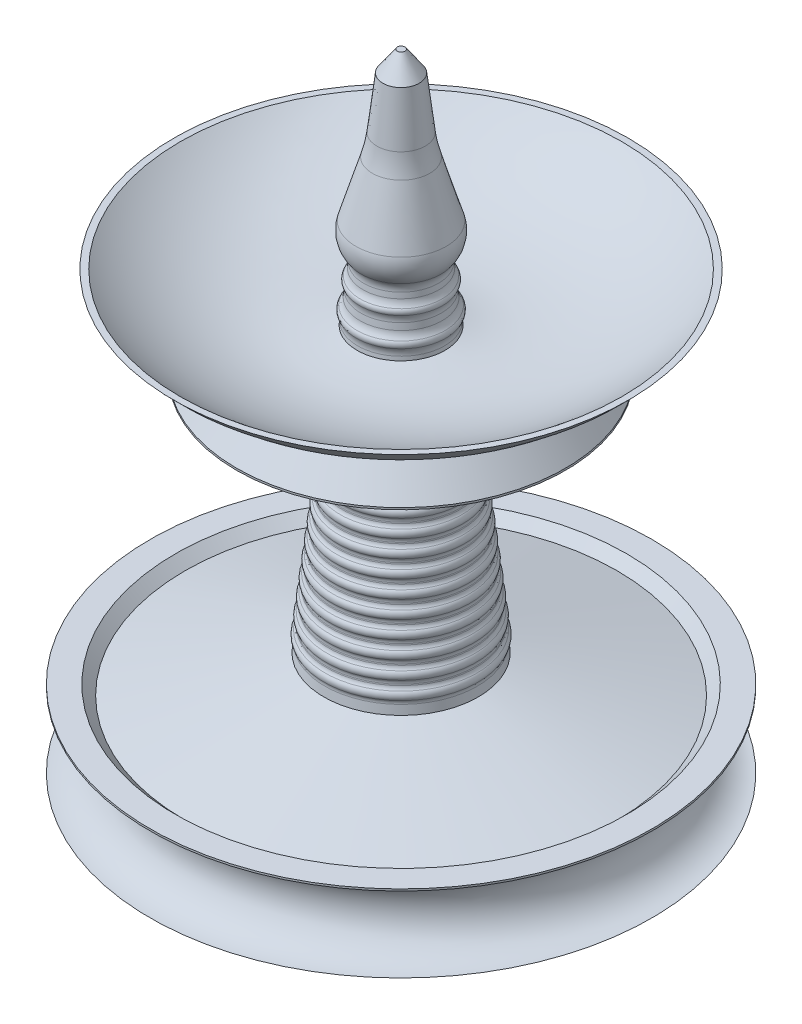
SolidWorks part; units mm, degrees
material "Brass"
ref_plane "Front Plane" through (0, 0, 0) normal (0, 0, 1) x (1, 0, 0)
ref_plane "Top Plane" through (0, 0, 0) normal (0, 1, 0) x (1, 0, 0)
ref_plane "Right Plane" through (0, 0, 0) normal (1, 0, 0) x (0, 0, -1)
sketch "Sketch1" plane through (0, 0, 0) normal (0, 0, 1) x (1, 0, 0)
  line L0 (0, 0) -> (0, 500)
  line L1 (0, 500) -> (3, 500)
  line L2 (3, 500) -> (14.4715, 483.617)
  line L3 (14.4715, 483.617) -> (19.2914, 442.6484)
  line L4 (22.8291, 425.58) -> (35.996, 381.7197)
  line L5 (0, 0) -> (200, 0)
  line L6 (36.0735, 300) -> (131.0735, 274.5448)
  line L7 (61.559, 83.3739) -> (172.2218, 53.7218)
  line L8 (200, 60) -> (200, 61.5)
  line L10 (180, 61.5) -> (172.2218, 53.7218)
  line L11 (200, 61.5) -> (180, 61.5)
  line L12 (0, 0) -> (0, 850) construction
  line L13 (100, 0) -> (0, 850) construction
  line L14 (131.0735, 274.5448) -> (131.0735, 276.0448)
  line L15 (131.0735, 276.0448) -> (107.7351, 309.3756)
  line L16 (181.1011, 348.035) -> (176.1011, 348.035)
  line L17 (61.559, 83.3739) -> (60.7337, 90.3882) construction
  line L18 (29.8182, 353.1703) -> (30.3152, 348.9456)
  line L19 (34.9705, 309.3756) -> (34.6202, 312.3532)
  line L20 (36.7723, 294.0603) -> (6.8742, 548.1942) construction
  line L21 (61.559, 83.3739) -> (60.7337, 90.3882)
  line L22 (32.1041, 333.7404) -> (32.693, 328.7343)
  line L23 (36.5361, 296.0681) -> (36.0735, 300)
  line L24 (37.9011, 293.1832) -> (39.42, 280.2723) construction
  line L25 (38.055, 283.1571) -> (37.7135, 286.0603) construction
  line L26 (38.055, 283.1571) -> (37.9497, 284.0526)
  line L27 (39.574, 270.2462) -> (39.4686, 271.1416) construction
  line L28 (39.574, 270.2462) -> (39.4686, 271.1416)
  line L29 (41.0929, 257.3352) -> (40.9876, 258.2306) construction
  line L30 (41.0929, 257.3352) -> (40.9876, 258.2306)
  line L31 (42.6118, 244.4243) -> (42.5065, 245.3197) construction
  line L32 (42.6118, 244.4243) -> (42.5065, 245.3197)
  line L33 (44.1308, 231.5133) -> (44.0254, 232.4087) construction
  line L34 (44.1308, 231.5133) -> (44.0254, 232.4087)
  line L35 (45.6497, 218.6023) -> (45.5444, 219.4978) construction
  line L36 (45.6497, 218.6023) -> (45.5444, 219.4978)
  line L37 (47.1687, 205.6914) -> (47.0633, 206.5868) construction
  line L38 (47.1687, 205.6914) -> (47.0633, 206.5868)
  line L39 (48.6876, 192.7804) -> (48.5822, 193.6758) construction
  line L40 (48.6876, 192.7804) -> (48.5822, 193.6758)
  line L41 (50.2065, 179.8695) -> (50.1012, 180.7649) construction
  line L42 (50.2065, 179.8695) -> (50.1012, 180.7649)
  line L43 (51.7255, 166.9585) -> (51.6201, 167.8539) construction
  line L44 (51.7255, 166.9585) -> (51.6201, 167.8539)
  line L45 (53.2444, 154.0476) -> (53.1391, 154.943) construction
  line L46 (53.2444, 154.0476) -> (53.1391, 154.943)
  line L47 (54.7633, 141.1366) -> (54.658, 142.032) construction
  line L48 (54.7633, 141.1366) -> (54.658, 142.032)
  line L49 (59.3201, 102.4037) -> (59.2148, 103.2991) construction
  line L50 (59.3201, 102.4037) -> (59.2148, 103.2991)
  line L51 (57.8012, 115.3147) -> (57.6959, 116.2101) construction
  line L52 (57.8012, 115.3147) -> (57.6959, 116.2101)
  line L53 (56.2823, 128.2256) -> (56.1769, 129.1211) construction
  line L54 (56.2823, 128.2256) -> (56.1769, 129.1211)
  arc A0 (35.996, 381.7197) -> (31.9237, 360.564) centre (13.731, 375.0357) cw
  arc A1 (200, 0) -> (200, 60) centre (200, 30) cw
  arc A2 (107.7351, 309.3756) -> (181.1011, 348.035) centre (91.9223, 428.3292) ccw
  arc A3 (176.1011, 348.035) -> (34.9705, 309.3756) centre (65.7611, 473.9074) cw
  arc A4 (19.2914, 442.6484) -> (22.8291, 425.58) centre (118.6064, 454.3325) ccw
  arc A5 (31.9237, 360.564) -> (29.8182, 353.1703) centre (39.7497, 354.3387) ccw
  arc A6 (32.5702, 343.7053) -> (33.0813, 339.361) centre (29.4996, 341.1418) cw
  arc A7 (35.1599, 323.2484) -> (35.7465, 318.2617) centre (31.893, 320.3362) cw
  arc A8 (34.6202, 312.3532) -> (35.7465, 318.2617) centre (44.5517, 313.5216) cw
  arc A9 (32.693, 328.7343) -> (35.1599, 323.2484) centre (42.6245, 329.9027) ccw
  arc A10 (33.0813, 339.361) -> (32.1041, 333.7404) centre (42.0356, 334.9088) ccw
  arc A11 (30.3152, 348.9456) -> (32.5702, 343.7053) centre (40.2467, 350.114) ccw
  arc A12 (37.9011, 293.1832) -> (38.6079, 287.1754) centre (34.3003, 289.7141) cw
  arc A13 (38.6079, 287.1754) -> (37.9497, 284.0526) centre (42.9154, 284.6368) ccw
  arc A14 (37.9011, 293.1832) -> (36.5361, 296.0681) centre (41.5019, 296.6523) cw
  arc A15 (39.42, 280.2723) -> (38.055, 283.1571) centre (43.0208, 283.7413) cw
  arc A16 (39.42, 280.2723) -> (40.1268, 274.2645) centre (35.8193, 276.8032) cw
  arc A17 (40.1268, 274.2645) -> (39.4686, 271.1416) centre (44.4344, 271.7258) ccw
  arc A18 (40.939, 267.3613) -> (39.574, 270.2462) centre (44.5397, 270.8304) cw
  arc A19 (40.939, 267.3613) -> (41.6458, 261.3535) centre (37.3382, 263.8922) cw
  arc A20 (41.6458, 261.3535) -> (40.9876, 258.2306) centre (45.9533, 258.8148) ccw
  arc A21 (42.4579, 254.4503) -> (41.0929, 257.3352) centre (46.0587, 257.9194) cw
  arc A22 (42.4579, 254.4503) -> (43.1647, 248.4426) centre (38.8571, 250.9813) cw
  arc A23 (43.1647, 248.4426) -> (42.5065, 245.3197) centre (47.4723, 245.9039) ccw
  arc A24 (43.9768, 241.5394) -> (42.6118, 244.4243) centre (47.5776, 245.0085) cw
  arc A25 (43.9768, 241.5394) -> (44.6836, 235.5316) centre (40.3761, 238.0703) cw
  arc A26 (44.6836, 235.5316) -> (44.0254, 232.4087) centre (48.9912, 232.9929) ccw
  arc A27 (45.4958, 228.6284) -> (44.1308, 231.5133) centre (49.0965, 232.0975) cw
  arc A28 (45.4958, 228.6284) -> (46.2026, 222.6207) centre (41.895, 225.1593) cw
  arc A29 (46.2026, 222.6207) -> (45.5444, 219.4978) centre (50.5101, 220.082) ccw
  arc A30 (47.0147, 215.7175) -> (45.6497, 218.6023) centre (50.6155, 219.1865) cw
  arc A31 (47.0147, 215.7175) -> (47.7215, 209.7097) centre (43.4139, 212.2484) cw
  arc A32 (47.7215, 209.7097) -> (47.0633, 206.5868) centre (52.0291, 207.171) ccw
  arc A33 (48.5336, 202.8065) -> (47.1687, 205.6914) centre (52.1344, 206.2756) cw
  arc A34 (48.5336, 202.8065) -> (49.2404, 196.7987) centre (44.9329, 199.3374) cw
  arc A35 (49.2404, 196.7987) -> (48.5822, 193.6758) centre (53.548, 194.2601) ccw
  arc A36 (50.0526, 189.8956) -> (48.6876, 192.7804) centre (53.6533, 193.3646) cw
  arc A37 (50.0526, 189.8956) -> (50.7594, 183.8878) centre (46.4518, 186.4265) cw
  arc A38 (50.7594, 183.8878) -> (50.1012, 180.7649) centre (55.0669, 181.3491) ccw
  arc A39 (51.5715, 176.9846) -> (50.2065, 179.8695) centre (55.1723, 180.4537) cw
  arc A40 (51.5715, 176.9846) -> (52.2783, 170.9768) centre (47.9708, 173.5155) cw
  arc A41 (52.2783, 170.9768) -> (51.6201, 167.8539) centre (56.5859, 168.4381) ccw
  arc A42 (53.0905, 164.0736) -> (51.7255, 166.9585) centre (56.6912, 167.5427) cw
  arc A43 (53.0905, 164.0736) -> (53.7973, 158.0659) centre (49.4897, 160.6046) cw
  arc A44 (53.7973, 158.0659) -> (53.1391, 154.943) centre (58.1048, 155.5272) ccw
  arc A45 (54.6094, 151.1627) -> (53.2444, 154.0476) centre (58.2102, 154.6318) cw
  arc A46 (54.6094, 151.1627) -> (55.3162, 145.1549) centre (51.0086, 147.6936) cw
  arc A47 (55.3162, 145.1549) -> (54.658, 142.032) centre (59.6237, 142.6162) ccw
  arc A48 (56.1283, 138.2517) -> (54.7633, 141.1366) centre (59.7291, 141.7208) cw
  arc A49 (56.1283, 138.2517) -> (56.8351, 132.244) centre (52.5276, 134.7826) cw
  arc A50 (56.8351, 132.244) -> (56.1769, 129.1211) centre (61.1427, 129.7053) ccw
  arc A51 (57.6473, 125.3408) -> (56.2823, 128.2256) centre (61.248, 128.8098) cw
  arc A52 (57.6473, 125.3408) -> (58.3541, 119.333) centre (54.0465, 121.8717) cw
  arc A53 (58.3541, 119.333) -> (57.6959, 116.2101) centre (62.6616, 116.7943) ccw
  arc A54 (59.1662, 112.4298) -> (57.8012, 115.3147) centre (62.767, 115.8989) cw
  arc A55 (59.1662, 112.4298) -> (59.873, 106.422) centre (55.5654, 108.9607) cw
  arc A56 (59.873, 106.422) -> (59.2148, 103.2991) centre (64.1806, 103.8833) ccw
  arc A57 (60.6851, 99.5188) -> (59.3201, 102.4037) centre (64.2859, 102.9879) cw
  arc A58 (60.6851, 99.5188) -> (61.3919, 93.5111) centre (57.0844, 96.0498) cw
  arc A59 (61.3919, 93.5111) -> (60.7337, 90.3882) centre (65.6995, 90.9724) ccw
  point P14 (150, 0)
  point P22 (180, 61.5)
  point P32 (20.3136, 433.9594)
  point P44 (29.279, 357.7537)
  point P51 (34.124, 316.5711)
  point P54 (33.1892, 324.5163)
  point P57 (31.6315, 337.7573)
  point P60 (30.7878, 344.9287)
  point P63 (0, 0)
  point P64 (0, 0)
  point P172 (0, 0)
  point P173 (0, 0)
  point P174 (0, 0)
  point P175 (0, 0)
  point P176 (0, 0)
  dimension "D8" = 30
  dimension "D19" = 5
  dimension "D20" = 120
  dimension "D21" = 100
  dimension "D22" = 10
  dimension "D23" = 4
  dimension "D25" = 10
  dimension "D26" = 5
  dimension "D27" = 5
  dimension "D1" = 500
  dimension "D2" = 3
  dimension "D3" = 35
  dimension "D4" = 20
  dimension "D5" = 50
  dimension "D6" = 10
  dimension "D7" = 200
  dimension "D9" = 1.5
  dimension "D10" = 300
  dimension "D11" = 20
  dimension "D12" = 850
  dimension "D13" = 135
  dimension "D14" = 120
  dimension "D15" = 11
  dimension "D16" = 50
  dimension "D17" = 95
  dimension "D18" = 1.5
  dimension "D24" = 8
  dimension "D28" = 13
  dimension "D29" = 16
revolve "Revolve3" add sketch "Sketch1" angle 360 about L12
